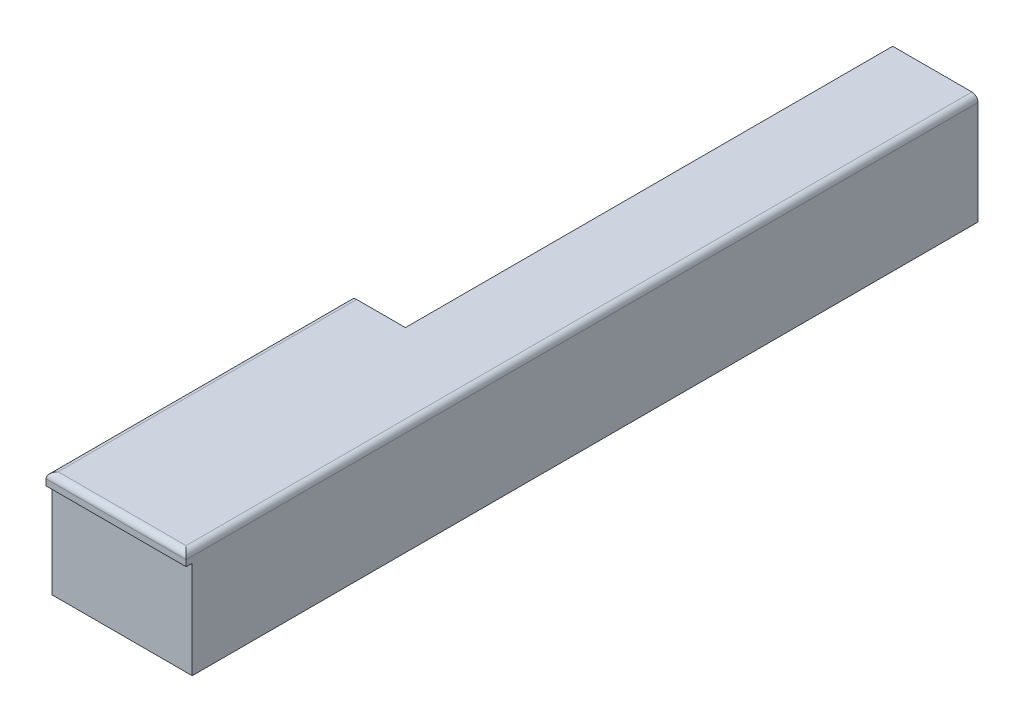
SolidWorks part; units mm, degrees
material "Pino"
ref_plane "Alzado" through (0, 0, 0) normal (0, 0, 1) x (1, 0, 0)
ref_plane "Planta" through (0, 0, 0) normal (0, 1, 0) x (1, 0, 0)
ref_plane "Vista lateral" through (0, 0, 0) normal (1, 0, 0) x (0, 0, -1)
sketch "Croquis2" plane through (0, 0, 0) normal (0, 1, 0) x (1, 0, 0)
  line L1 (0, 0) -> (23, 0)
  line L2 (0, 0) -> (0, 130)
  line L3 (0, 130) -> (23, 130)
  line L4 (23, 0) -> (23, 130)
  line L5 (0, 130) -> (9, 130)
  line L6 (0, 115.866) -> (0, 50)
  line L7 (23, 50) -> (20, 50)
  line L9 (0, 50) -> (9, 50)
  line L10 (0, 130) -> (0, 50)
  line L11 (0, 50) -> (9, 50)
  line L12 (9, 130) -> (9, 50)
  dimension "D1" = 23
  dimension "D2" = 130
  dimension "D3" = 50
  dimension "D4" = 14
  dimension "D5" = 9
extrude "Saliente-Extruir1" add sketch "Croquis2" along normal blind 18
sketch "Croquis3" plane through (0, 0, 0) normal (0, 0, 1) x (1, 0, 0)
  line L0 (23, 18) -> (23, 0) construction
  line L1 (0, 0) -> (23, 0)
  line L2 (0, 0) -> (0, 16)
  line L3 (0, 16) -> (23, 16)
  line L4 (23, 0) -> (23, 16)
  dimension "D1" = 16
extrude "Cortar-Extruir1" cut sketch "Croquis3" against normal blind 1
fillet "Redondeo1" radius 1 3 edges at (11.5, 18, 0) (23, 18, -65) (0, 18, -25)
